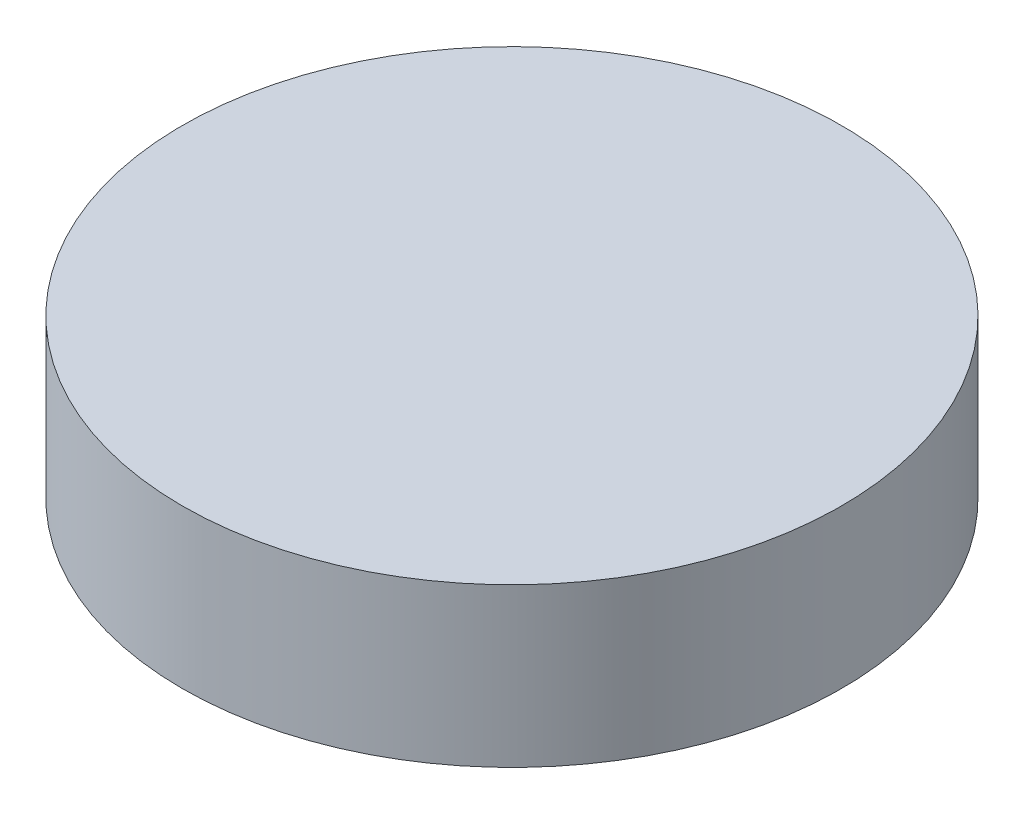
SolidWorks part; units mm, degrees
ref_plane "Front Plane" through (0, 0, 0) normal (0, 0, 1) x (1, 0, 0)
ref_plane "Top Plane" through (0, 0, 0) normal (0, 1, 0) x (1, 0, 0)
ref_plane "Right Plane" through (0, 0, 0) normal (1, 0, 0) x (0, 0, -1)
other "Configuration Table"
sketch "Sketch1" plane through (0, 0, 0) normal (0, 1, 0) x (1, 0, 0)
  circle A0 centre (650, 770) radius 25
extrude "TOPPING_ayar_ayagi_4" add sketch "Sketch1" along normal blind 12 separate body
